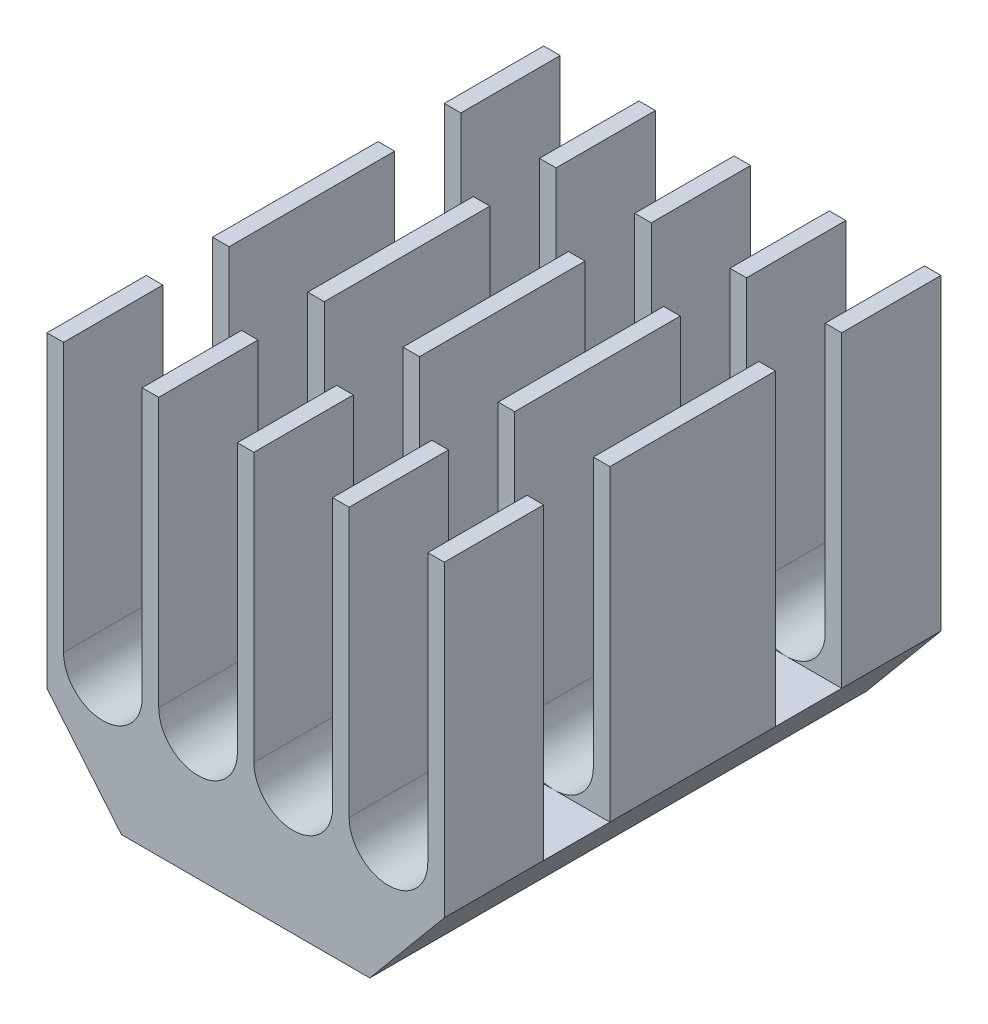
SolidWorks part; units mm, degrees
ref_plane "Ebene vorne" through (0, 0, 0) normal (0, 0, 1) x (1, 0, 0)
ref_plane "Ebene oben" through (0, 0, 0) normal (0, 1, 0) x (1, 0, 0)
ref_plane "Ebene rechts" through (0, 0, 0) normal (1, 0, 0) x (0, 0, -1)
sketch "Skizze1" plane through (0, 0, 0) normal (0, 0, 1) x (1, 0, 0)
  line L0 (-6, 12) -> (-6, 2.7)
  line L1 (-6, 2.7) -> (-3.75, 0)
  line L2 (-3.75, 0) -> (3.75, 0)
  line L3 (3.75, 0) -> (6, 2.7)
  line L4 (6, 2.7) -> (6, 12)
  line L5 (6, 12) -> (-6, 12)
  line L6 (0, -1000) -> (0, 49000) construction
  dimension "D1" = 12
  dimension "D2" = 7.5
  dimension "D3" = 2.7
  dimension "D4" = 12
extrude "Aufsatz-Linear austragen1" add sketch "Skizze1" along normal mid plane 15
sketch "Skizze2" plane through (0, 0, 7.5) normal (0, 0, 1) x (1, 0, 0)
  line L0 (-4.3125, 12) -> (-4.3125, 3.8875) construction
  line L1 (-3.125, 12) -> (-3.125, 3.8875)
  line L2 (-5.5, 12) -> (-5.5, 3.8875)
  line L3 (-6, 12) -> (-6, 2.7) construction
  line L4 (6, 12) -> (-6, 12) construction
  line L5 (-6, 2.7) -> (6, 2.7) construction
  line L6 (-1.4375, 12) -> (-1.4375, 3.8875) construction
  line L7 (-0.25, 12) -> (-0.25, 3.8875)
  line L8 (-2.625, 12) -> (-2.625, 3.8875)
  line L9 (1.4375, 12) -> (1.4375, 3.8875) construction
  line L10 (2.625, 12) -> (2.625, 3.8875)
  line L11 (0.25, 12) -> (0.25, 3.8875)
  line L12 (4.3125, 12) -> (4.3125, 3.8875) construction
  line L13 (5.5, 12) -> (5.5, 3.8875)
  line L14 (3.125, 12) -> (3.125, 3.8875)
  line L15 (6, 2.7) -> (6, 12) construction
  arc A0 (-3.125, 12) -> (-5.5, 12) centre (-4.3125, 12) ccw
  arc A1 (-5.5, 3.8875) -> (-3.125, 3.8875) centre (-4.3125, 3.8875) ccw
  arc A2 (-0.25, 12) -> (-2.625, 12) centre (-1.4375, 12) ccw
  arc A3 (-2.625, 3.8875) -> (-0.25, 3.8875) centre (-1.4375, 3.8875) ccw
  arc A4 (2.625, 12) -> (0.25, 12) centre (1.4375, 12) ccw
  arc A5 (0.25, 3.8875) -> (2.625, 3.8875) centre (1.4375, 3.8875) ccw
  arc A6 (5.5, 12) -> (3.125, 12) centre (4.3125, 12) ccw
  arc A7 (3.125, 3.8875) -> (5.5, 3.8875) centre (4.3125, 3.8875) ccw
  point P2 (-4.3125, 7.9438)
  point P18 (-1.4375, 7.9438)
  point P25 (1.4375, 7.9438)
  point P32 (4.3125, 7.9438)
  dimension "D1" = 0.5
  dimension "D3" = 0.5
  dimension "D4" = 0.5
  dimension "D2" = 4
extrude "Schnitt-Linear austragen1" cut sketch "Skizze2" against normal up to surface (15 mm away) up to face at (0, 4.9, -7.5)
sketch "Skizze3" plane through (6, 0, 0) normal (1, 0, 0) x (0, 0, -1)
  line L0 (-7.5, 12) -> (7.5, 12) construction
  line L1 (-4.5, 12) -> (-2.5, 12)
  line L2 (-4.5, 12) -> (-4.5, 2.7)
  line L3 (-4.5, 2.7) -> (-2.5, 2.7)
  line L4 (-2.5, 12) -> (-2.5, 2.7)
  line L5 (-7.5, 2.7) -> (7.5, 2.7) construction
  line L6 (2.5, 12) -> (2.5, 2.7)
  line L7 (2.5, 12) -> (4.5, 12)
  line L8 (4.5, 12) -> (4.5, 2.7)
  line L9 (2.5, 2.7) -> (4.5, 2.7)
  line L10 (0, -1000) -> (0, 49000) construction
  line L11 (-7.5, 2.7) -> (-7.5, 12) construction
  line L12 (9.5, 12) -> (9.5, 2.7)
  line L13 (9.5, 12) -> (11.5, 12)
  line L14 (11.5, 12) -> (11.5, 2.7)
  line L15 (9.5, 2.7) -> (11.5, 2.7)
  line L16 (16.5, 12) -> (16.5, 2.7)
  line L17 (16.5, 12) -> (18.5, 12)
  line L18 (18.5, 12) -> (18.5, 2.7)
  line L19 (16.5, 2.7) -> (18.5, 2.7)
  dimension "D2" = 3
  dimension "D3" = 5
  dimension "D1" = 4
extrude "Schnitt-Linear austragen2" cut sketch "Skizze3" against normal up to surface (12 mm away) up to face at (-6, 7.35, 0)
sketch "Skizze4" plane through (0, 0, 0) normal (0, -1, 0) x (1, 0, 0)
  line L0 (-3.75, 7.5) -> (3.75, 7.5) construction
  line L1 (-3.65, -7.4) -> (3.65, -7.4)
  line L2 (-3.65, -7.4) -> (-3.65, 7.4)
  line L3 (-3.65, 7.4) -> (3.65, 7.4)
  line L4 (3.65, -7.4) -> (3.65, 7.4)
  line L5 (-3.65, -7.4) -> (3.65, 7.4) construction
  line L6 (-3.65, 7.4) -> (3.65, -7.4) construction
  line L7 (-3.75, 7.5) -> (-3.75, -7.5) construction
  point P0 (0, 0)
  dimension "D1" = 0.1
  dimension "D2" = 0.1
extrude "Aufsatz-Linear austragen2" add sketch "Skizze4" along normal blind 0.1
